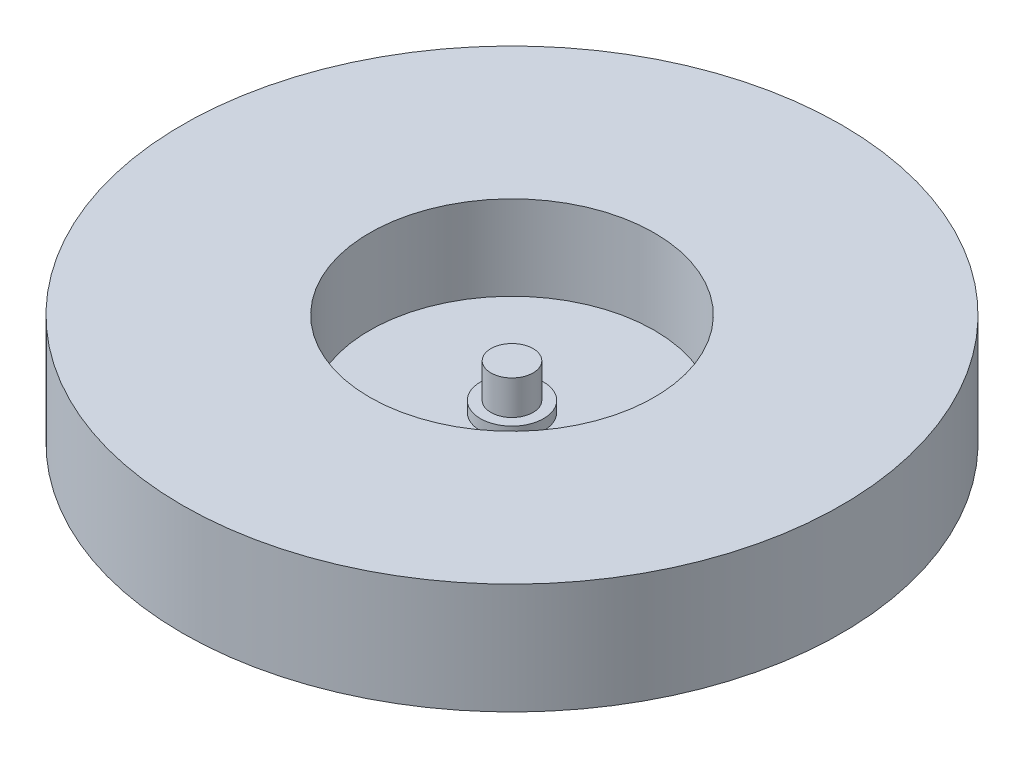
SolidWorks part; units mm, degrees
ref_plane "Front Plane" through (0, 0, 0) normal (0, 0, 1) x (1, 0, 0)
ref_plane "Top Plane" through (0, 0, 0) normal (0, 1, 0) x (1, 0, 0)
ref_plane "Right Plane" through (0, 0, 0) normal (1, 0, 0) x (0, 0, -1)
sketch "Sketch1" plane through (0, 0, 0) normal (0, 1, 0) x (1, 0, 0)
  circle A0 centre (0, 0) radius 62.5
  dimension "D1" = 125
extrude "Boss-Extrude1" add sketch "Sketch1" along normal blind 21
sketch "Sketch2" plane through (0, 21, 0) normal (0, 1, 0) x (1, 0, 0)
  circle A0 centre (0, 0) radius 27
  circle A1 centre (0, 0) radius 6
extrude "Cut-Extrude1" cut sketch "Sketch2" against normal blind 16
sketch "Sketch3" plane through (0, 21, 0) normal (0, 1, 0) x (1, 0, 0)
  circle A0 centre (0, 0) radius 6
  circle A1 centre (0, 0) radius 4
extrude "Cut-Extrude2" cut sketch "Sketch3" against normal blind 14
sketch "Sketch4" plane through (0, 21, 0) normal (0, 1, 0) x (1, 0, 0)
  circle A0 centre (0, 0) radius 4
extrude "Cut-Extrude3" cut sketch "Sketch4" against normal blind 7.5
